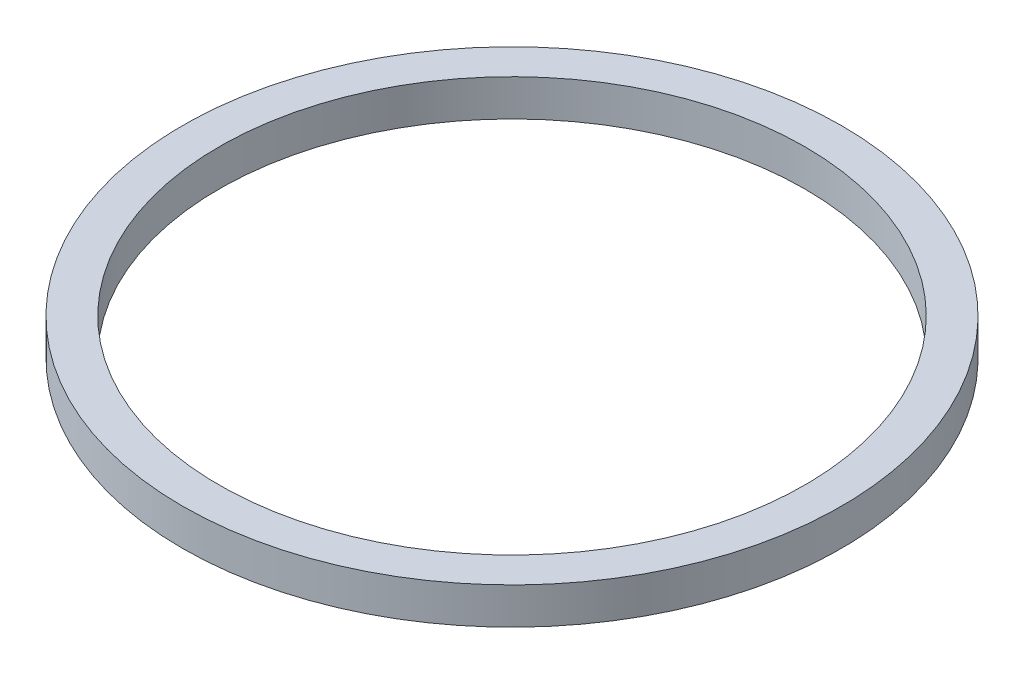
SolidWorks part; units mm, degrees
ref_plane "前视基准面" through (0, 0, 0) normal (0, 0, 1) x (1, 0, 0)
ref_plane "上视基准面" through (0, 0, 0) normal (0, 1, 0) x (1, 0, 0)
ref_plane "右视基准面" through (0, 0, 0) normal (1, 0, 0) x (0, 0, -1)
sketch "草图1" plane through (0, 0, 0) normal (0, 1, 0) x (1, 0, 0)
  circle A0 centre (0, 0) radius 152.4
  circle A1 centre (0, 0) radius 171.45
  dimension "D1" = 304.8
  dimension "D2" = 342.9
extrude "凸台-拉伸1" add sketch "草图1" along normal blind 19.05
